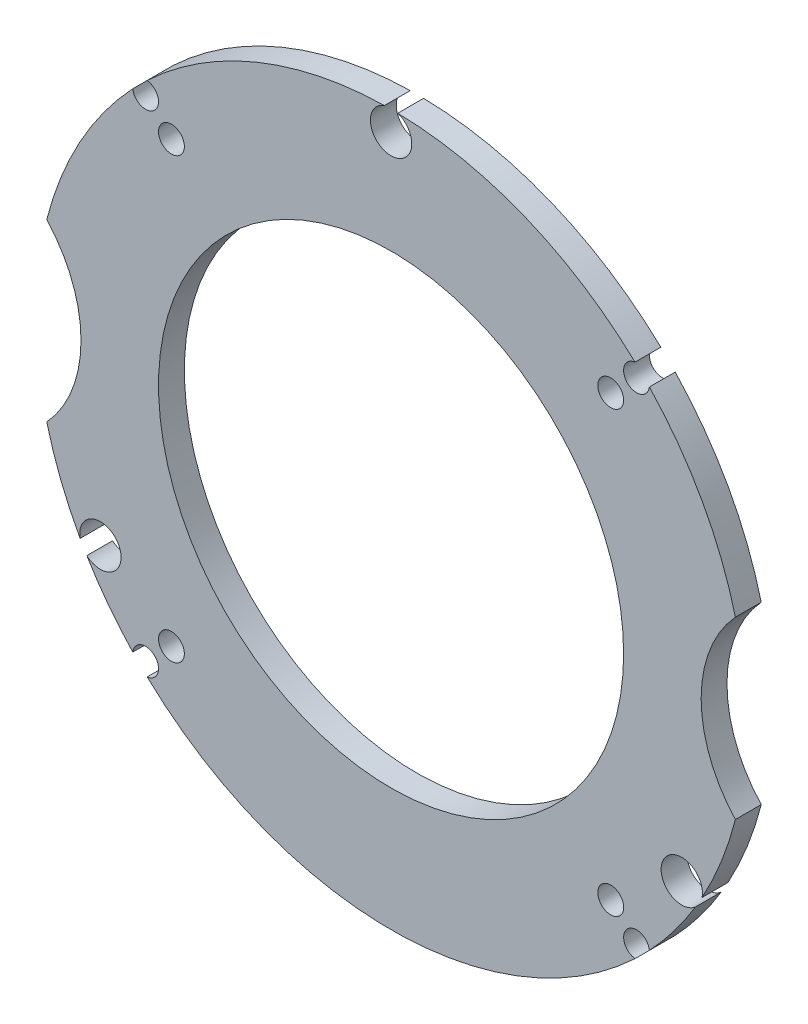
SolidWorks part; units mm, degrees
ref_plane "Front Plane" through (0, 0, 0) normal (0, 0, 1) x (1, 0, 0)
ref_plane "Top Plane" through (0, 0, 0) normal (0, 1, 0) x (1, 0, 0)
ref_plane "Right Plane" through (0, 0, 0) normal (1, 0, 0) x (0, 0, -1)
sketch "Sketch1" plane through (0, 0, 0) normal (0, 0, 1) x (1, 0, 0)
  line L4 (0, 39) -> (0, -40.7055) construction
  line L5 (-43.0364, 0) -> (51.1093, 0) construction
  arc A0 (-27.5, 0) -> (27.5, 0) centre (0, 0) ccw
  arc A1 (27.5, 0) -> (-27.5, 0) centre (0, 0) ccw
  circle A2 centre (0, 0) radius 18
  point P2 (29, 0)
  point P4 (29, 0.5337)
  point P5 (-29, 0)
  point P6 (-29, -0.4706)
  dimension "D1" = 55
  dimension "D4" = 36
extrude "Boss-Extrude1" add sketch "Sketch1" along normal blind 2
sketch "Sketch2" plane through (0, 0, 2) normal (0, 0, 1) x (1, 0, 0)
  line L0 (-33.5817, 0) -> (33.9726, 0) construction
  line L1 (0, 25.9808) -> (0, 0) construction
  line L2 (-22.5, -12.9904) -> (0, 0) construction
  circle A0 centre (0, 25.9808) radius 1.6
  circle A1 centre (-22.5, -12.9904) radius 1.6
  circle A3 centre (22.5, -12.9904) radius 1.6
  point P3 (0, -1.126)
  point P9 (0, 22.9473)
  point P10 (0, 24.06)
  dimension "D1" = 3.2
  dimension "D2" = 45
  dimension "D3" = 45
extrude "Cut-Extrude1" cut sketch "Sketch2" against normal blind 2
sketch "Sketch3" plane through (0, 0, 2) normal (0, 0, 1) x (1, 0, 0)
  line L0 (0, 15.6309) -> (0, -13.6849) construction
  line L1 (-12.5553, 0) -> (11.836, 0) construction
  point P5 (-17, 17)
  point P6 (17, 17)
  point P7 (17, -17)
  point P8 (-17, -17)
  point P9 (19, 19)
  point P10 (19, -19)
  point P11 (-19, -19)
  point P13 (-19, 19)
  dimension "D1" = 34
  dimension "D2" = 34
  dimension "D3" = 38
  dimension "D4" = 38
hole_wizard "Ø2.0mm Dowel Hole1" positions "3DSketch1" profile "Sketch4" hole size "Ø2.0" standard "ANSI Metric" end condition through all
sketch3d "3DSketch1"
  point P0 (-19, 19, 2)
  point P3 (-17, 17, 2)
  point P6 (17, 17, 2)
  point P9 (19, 19, 2)
  point P12 (17, -17, 2)
  point P15 (19, -19, 2)
  point P18 (-19, -19, 2)
  point P21 (-17, -17, 2)
sketch "Sketch4" plane through (-19, 19, 2) normal (1, 0, 0) x (0, -1, 0)
  line L0 (0, 0) -> (0, 2)
  line L1 (0, 2) -> (1, 2)
  line L2 (1, 2) -> (1, 0)
  line L5 (1, 0) -> (0, 0)
  line L11 (0, -6.35) -> (0, 107.95) construction
  dimension "Thru Hole Dia." = 2
  dimension "Thru Hole Depth" = 2
sketch "스케치1" plane through (0, 0, 0) normal (0, 0, 1) x (1, 0, 0)
  line L0 (-36.0943, 0) -> (35.7308, 0) construction
  line L2 (0, 17.2396) -> (0, -16.7084) construction
  circle A0 centre (-34, 0) radius 10
  circle A1 centre (34, 0) radius 10
  point P7 (24, 0)
  point P8 (-24, 0)
  dimension "D1" = 20
  dimension "D2" = 48
extrude "컷-돌출1" cut sketch "스케치1" along normal through all
